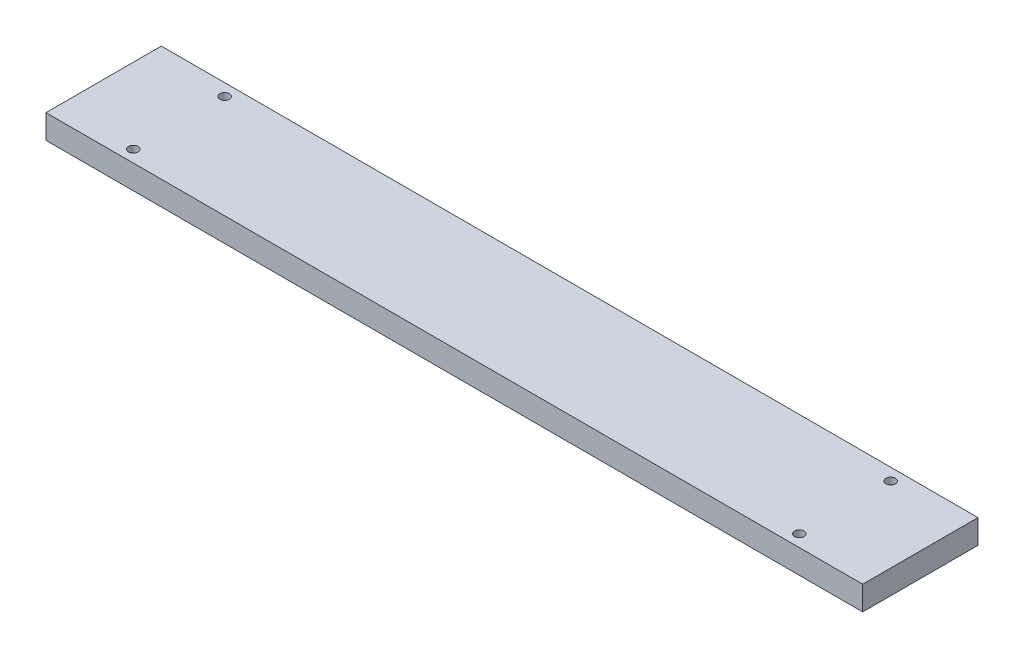
SolidWorks part; units mm, degrees
ref_plane "Front Plane" through (0, 0, 0) normal (0, 0, 1) x (1, 0, 0)
ref_plane "Top Plane" through (0, 0, 0) normal (0, 1, 0) x (1, 0, 0)
ref_plane "Right Plane" through (0, 0, 0) normal (1, 0, 0) x (0, 0, -1)
sketch "Sketch1" plane through (0, 0, 0) normal (0, 1, 0) x (1, 0, 0)
  line L1 (-425, 60) -> (425, 60)
  line L2 (-425, 60) -> (-425, -60)
  line L3 (-425, -60) -> (425, -60)
  line L4 (425, 60) -> (425, -60)
  line L5 (-425, 60) -> (425, -60) construction
  line L6 (-425, -60) -> (425, 60) construction
  point P0 (0, 0)
  dimension "D1" = 120
  dimension "D2" = 850
extrude "Boss-Extrude1" add sketch "Sketch1" along normal blind 25
sketch "Sketch2" plane through (0, 25, 0) normal (0, 1, 0) x (1, 0, 0)
  line L0 (425, 60) -> (-425, 60) construction
  line L1 (-425, -60) -> (425, -60) construction
  line L2 (0, 114.8321) -> (0, -128.4424) construction
  circle A0 centre (-346.6168, 47.5) radius 5
  circle A1 centre (-346.6168, -47.5) radius 5
  circle A2 centre (346.6168, -47.5) radius 5
  circle A3 centre (346.6168, 47.5) radius 5
  dimension "D3" = 10
  dimension "D4" = 10
  dimension "D1" = 12.5
  dimension "D2" = 12.5
extrude "Cut-Extrude1" cut sketch "Sketch2" against normal blind 25
